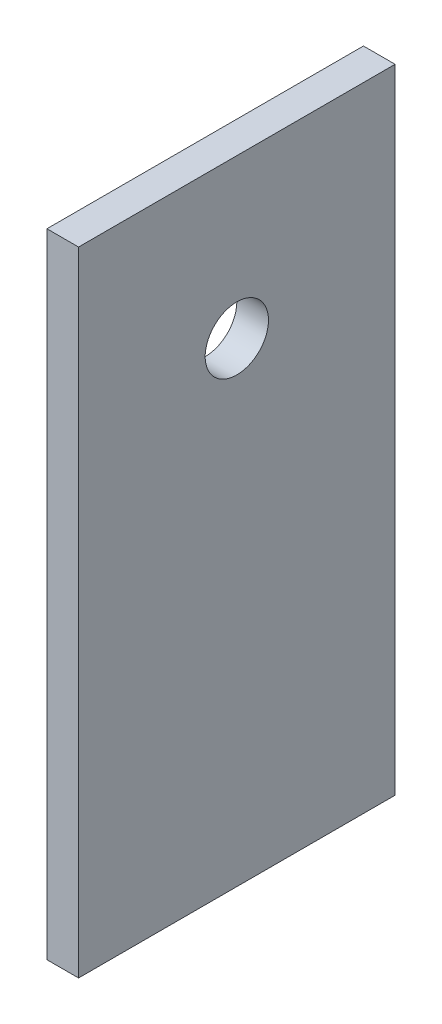
SolidWorks part; units mm, degrees
ref_plane "Front Plane" through (0, 0, 0) normal (0, 0, 1) x (1, 0, 0)
ref_plane "Top Plane" through (0, 0, 0) normal (0, 1, 0) x (1, 0, 0)
ref_plane "Right Plane" through (0, 0, 0) normal (1, 0, 0) x (0, 0, -1)
sketch "Sketch1" plane through (0, 0, 0) normal (1, 0, 0) x (0, 0, -1)
  line L0 (0, -42.5) -> (0, -66.5) construction
  line L1 (-20, -42.5) -> (20, -42.5)
  line L2 (-20, -42.5) -> (-20, -122.5)
  line L3 (-20, -122.5) -> (20, -122.5)
  line L4 (20, -42.5) -> (20, -122.5)
  circle A0 centre (0, -62.5) radius 4
  point P0 (0, 0)
  dimension "D3" = 80
  dimension "D1" = 20
  dimension "D2" = 40
  dimension "D7" = 20
extrude "Boss-Extrude1" add sketch "Sketch1" along normal blind 4
